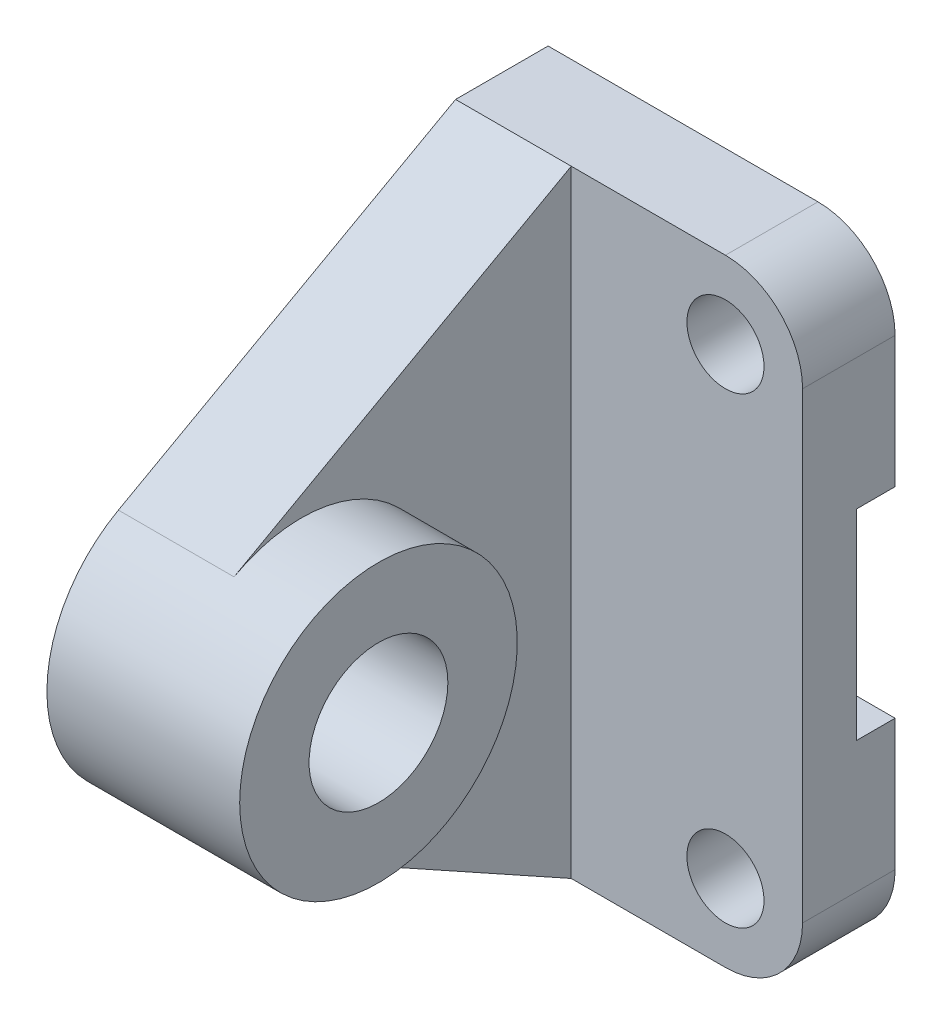
SolidWorks part; units mm, degrees
ref_plane "前视基准面" through (0, 0, 0) normal (0, 0, 1) x (1, 0, 0)
ref_plane "上视基准面" through (0, 0, 0) normal (0, 1, 0) x (1, 0, 0)
ref_plane "右视基准面" through (0, 0, 0) normal (1, 0, 0) x (0, 0, -1)
sketch "草图2" plane through (0, 0, 0) normal (1, 0, 0) x (0, 0, -1)
  line L0 (0, 40) -> (-12, 40)
  line L1 (-12, 40) -> (-12, -40)
  line L2 (-12, -40) -> (0, -40)
  line L8 (0, 40) -> (0, -40)
  point P4 (0, 0)
  dimension "D2" = 80
  dimension "D3" = 12
extrude "凸台-拉伸1" add sketch "草图2" along normal blind 45
fillet "圆角1" radius 10 2 edges at (45, 40, 6) (45, -40, 6)
sketch "草图3" plane through (0, 0, 12) normal (0, 0, 1) x (1, 0, 0)
  circle A0 centre (35, 30) radius 5
  circle A1 centre (35, -30) radius 5
  dimension "D1" = 10
  dimension "D2" = 10
extrude "切除-拉伸1" cut sketch "草图3" against normal through all
sketch "草图5" plane through (45, 0, 0) normal (1, 0, 0) x (0, 0, -1)
  line L1 (5, -13) -> (-5, -13)
  line L2 (5, -13) -> (5, 13)
  line L3 (5, 13) -> (-5, 13)
  line L4 (-5, -13) -> (-5, 13)
  line L5 (5, -13) -> (-5, 13) construction
  line L6 (5, 13) -> (-5, -13) construction
  point P0 (0, 0)
  dimension "D1" = 26
  dimension "D2" = 10
extrude "切除-拉伸2" cut sketch "草图5" against normal through all
sketch "草图6" plane through (0, 0, 0) normal (-1, 0, 0) x (0, 0, 1)
  circle A0 centre (47, 0) radius 18
  point P2 (0, 0)
  point P4 (0, 0)
  dimension "D1" = 36
  dimension "D2" = 47
extrude "凸台-拉伸2" add sketch "草图6" against normal blind 25 separate body
sketch "草图7" plane through (0, 0, 0) normal (-1, 0, 0) x (0, 0, 1)
  line L0 (12, 40) -> (55.7318, 15.7403)
  line L1 (12, -40) -> (55.7318, -15.7403)
  line L2 (12, 40) -> (12, -40)
  circle A0 centre (47, 0) radius 18 construction
  arc A1 (55.7318, -15.7403) -> (55.7318, 15.7403) centre (47, 0) ccw
extrude "凸台-拉伸3" add sketch "草图7" against normal blind 15
sketch "草图8" plane through (25, 0, 0) normal (1, 0, 0) x (0, 0, -1)
  circle A0 centre (-47, 0) radius 9
  dimension "D1" = 18
extrude "切除-拉伸3" cut sketch "草图8" against normal through all
